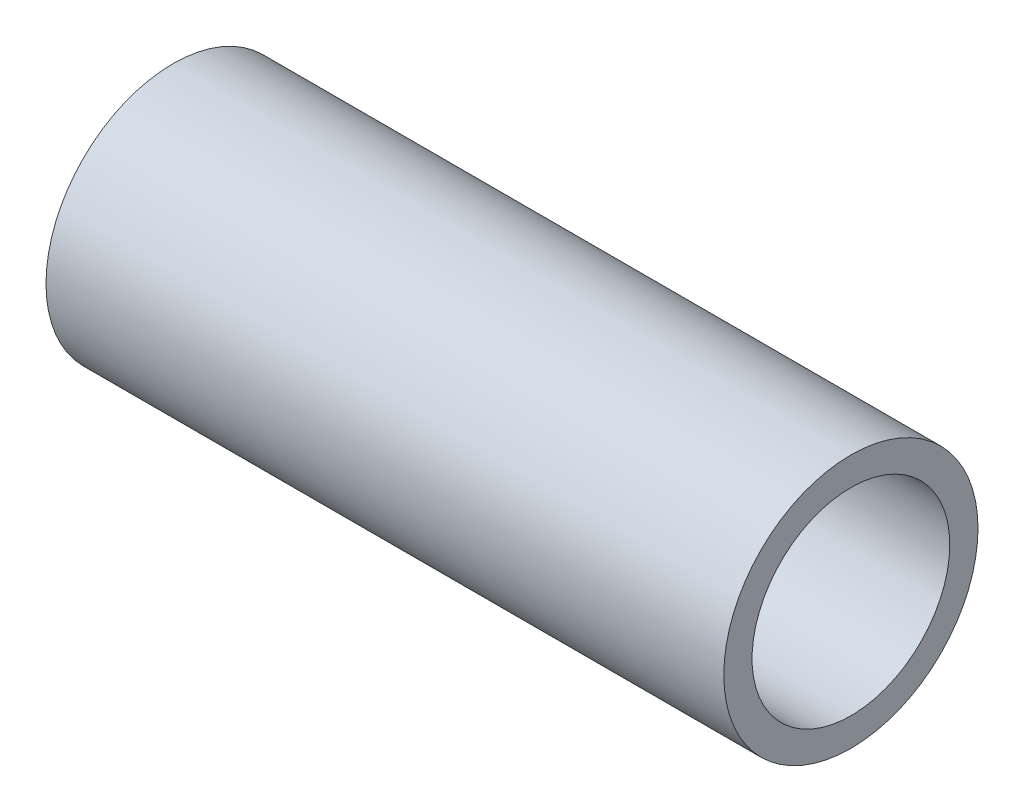
SolidWorks part; units mm, degrees
ref_plane "Front Plane" through (0, 0, 0) normal (0, 0, 1) x (1, 0, 0)
ref_plane "Top Plane" through (0, 0, 0) normal (0, 1, 0) x (1, 0, 0)
ref_plane "Right Plane" through (0, 0, 0) normal (1, 0, 0) x (0, 0, -1)
sketch "Sketch1" plane through (0, 0, 0) normal (1, 0, 0) x (0, 0, -1)
  circle A0 centre (0, 0) radius 7
  circle A1 centre (0, 0) radius 9
  dimension "D1" = 18
  dimension "D2" = 14
extrude "Boss-Extrude1" add sketch "Sketch1" along normal mid plane 48
